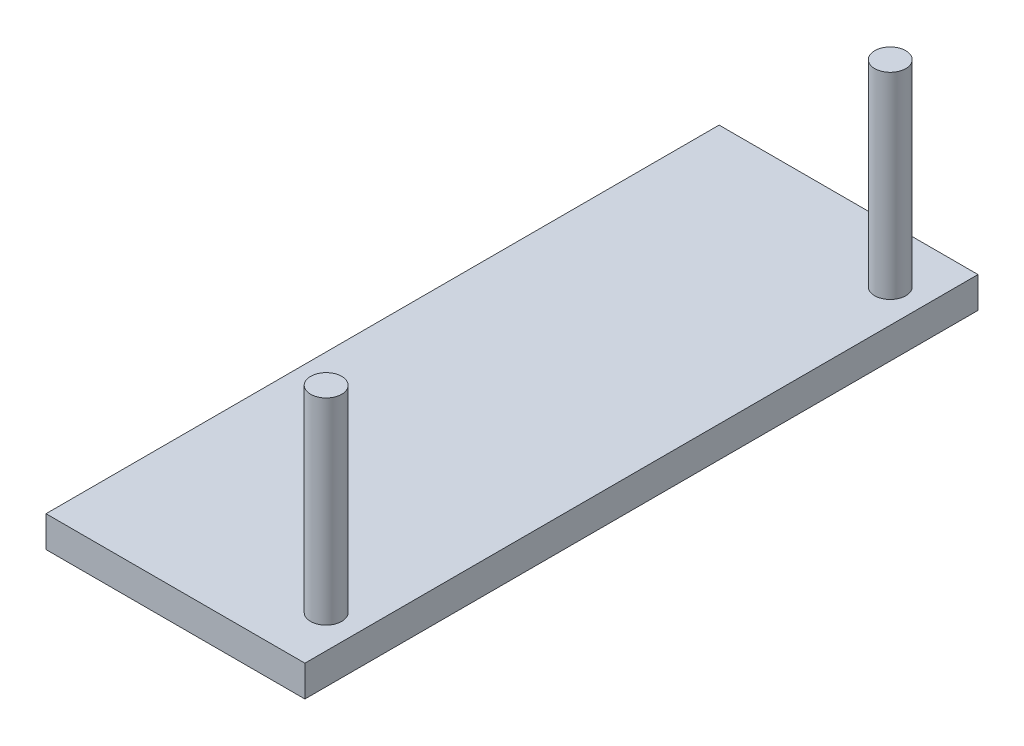
SolidWorks part; units mm, degrees
ref_plane "Front Plane" through (0, 0, 0) normal (0, 0, 1) x (1, 0, 0)
ref_plane "Top Plane" through (0, 0, 0) normal (0, 1, 0) x (1, 0, 0)
ref_plane "Right Plane" through (0, 0, 0) normal (1, 0, 0) x (0, 0, -1)
sketch "Sketch1" plane through (0, 0, 0) normal (0, 1, 0) x (1, 0, 0)
  line L1 (-12.5, -32.5) -> (12.5, -32.5)
  line L2 (-12.5, -32.5) -> (-12.5, 32.5)
  line L3 (-12.5, 32.5) -> (12.5, 32.5)
  line L4 (12.5, -32.5) -> (12.5, 32.5)
  line L5 (-12.5, -32.5) -> (12.5, 32.5) construction
  line L6 (-12.5, 32.5) -> (12.5, -32.5) construction
  point P0 (0, 0)
  dimension "D1" = 65
  dimension "D2" = 25
extrude "Boss-Extrude1" add sketch "Sketch1" along normal blind 3
sketch "Sketch2" plane through (0, 3, 0) normal (0, 1, 0) x (1, 0, 0)
  line L0 (-70.6517, 0) -> (70.6517, 0) construction
  line L1 (12.5, -32.5) -> (12.5, 32.5) construction
  circle A0 centre (9.2897, 27.2349) radius 1.5
  circle A1 centre (9.2897, -27.2349) radius 1.5
  point P8 (0, 0)
  dimension "D1" = 3
  dimension "D2" = 3.2103
  dimension "D3" = 54.4698
extrude "Boss-Extrude2" add sketch "Sketch2" along normal blind 19
